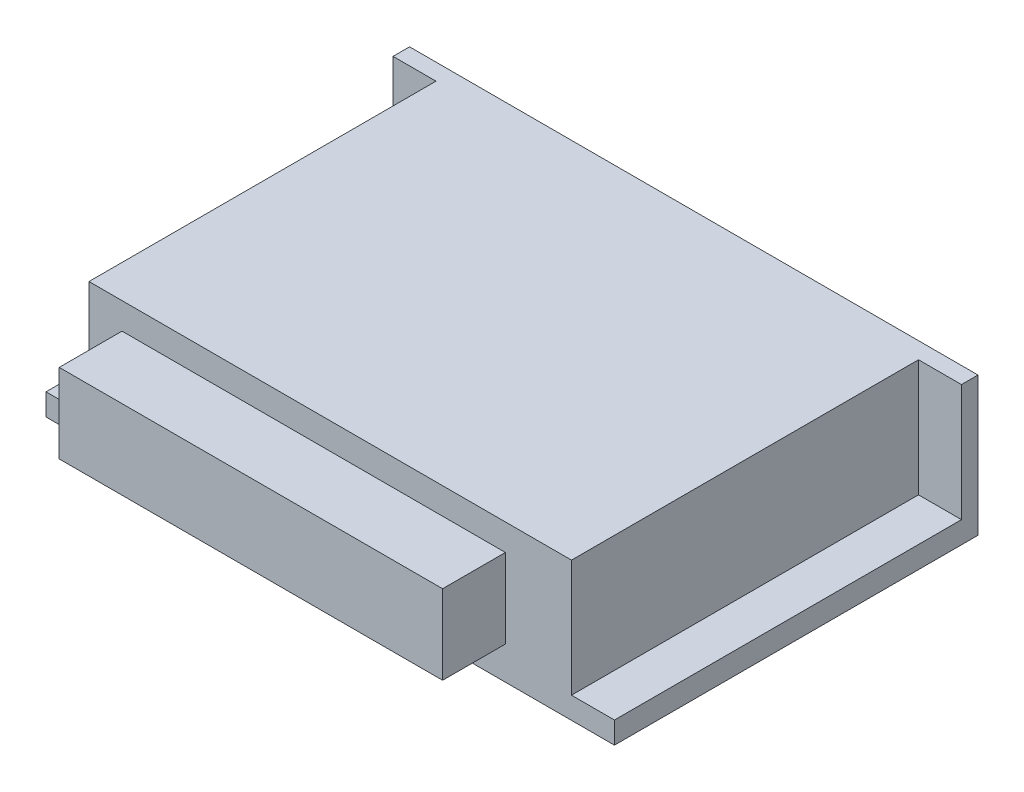
SolidWorks part; units mm, degrees
ref_plane "Front" through (0, 0, 0) normal (0, 0, 1) x (1, 0, 0)
ref_plane "Top" through (0, 0, 0) normal (0, 1, 0) x (1, 0, 0)
ref_plane "Right" through (0, 0, 0) normal (1, 0, 0) x (0, 0, -1)
sketch "Sketch1" plane through (0, 0, 0) normal (0, 1, 0) x (1, 0, 0)
  line L1 (-43, -27.5) -> (43, -27.5)
  line L2 (-43, -27.5) -> (-43, 27.5)
  line L3 (-43, 27.5) -> (43, 27.5)
  line L4 (43, -27.5) -> (43, 27.5)
  line L5 (-43, -27.5) -> (43, 27.5) construction
  line L6 (-43, 27.5) -> (43, -27.5) construction
  point P0 (0, 0)
  dimension "D1" = 86
  dimension "D2" = 55
extrude "Boss-Extrude1" add sketch "Sketch1" along normal blind 3.3
sketch "Sketch2" plane through (0, 3.3, 0) normal (0, 1, 0) x (1, 0, 0)
  line L0 (43, 27.5) -> (-43, 27.5) construction
  line L1 (-48.75, 27.5) -> (48.75, 27.5)
  line L2 (-36.5, 25) -> (-36.5, -27.5)
  line L3 (-36.5, -27.5) -> (36.5, -27.5)
  line L4 (36.5, 25) -> (36.5, -27.5)
  line L5 (-43, 27.5) -> (-43, -27.5) construction
  line L6 (-43, -27.5) -> (43, -27.5) construction
  line L7 (43, -27.5) -> (43, 27.5) construction
  line L8 (-43, 27.5) -> (43, 27.5)
  line L9 (-43, 27.5) -> (-43, 25)
  line L10 (-43, 25) -> (-36.5, 25)
  line L11 (43, 27.5) -> (43, 25)
  line L12 (36.5, 25) -> (43, 25)
  point P6 (0, -27.5)
  line M10 (43, -27.5) -> (43, 27.5)
  line M11 (43, 27.5) -> (-43, 27.5)
  line M12 (-43, 27.5) -> (-43, -27.5)
  line M13 (-43, -27.5) -> (43, -27.5)
  dimension "D1" = 6.5
  dimension "D2" = 2.5
extrude "Boss-Extrude2" add sketch "Sketch2" along normal offset from surface (17.7 mm away) 21 contours L4 L12 L10 L2 M10 M11 M12 M13 up to face at (0, 0, 0)
sketch "Sketch3" plane through (0, 0, 27.5) normal (0, 0, 1) x (1, 0, 0)
  line L1 (-31.5, 5) -> (26.5, 5)
  line L2 (-31.5, 5) -> (-31.5, 17)
  line L3 (-31.5, 17) -> (26.5, 17)
  line L4 (26.5, 5) -> (26.5, 17)
  line L5 (-36.5, 21) -> (-36.5, 3.3) construction
  line L6 (36.5, 21) -> (-36.5, 21) construction
  dimension "D1" = 58
  dimension "D2" = 5
  dimension "D3" = 4
  dimension "D4" = 12
extrude "Boss-Extrude3" add sketch "Sketch3" along normal blind 9.5
